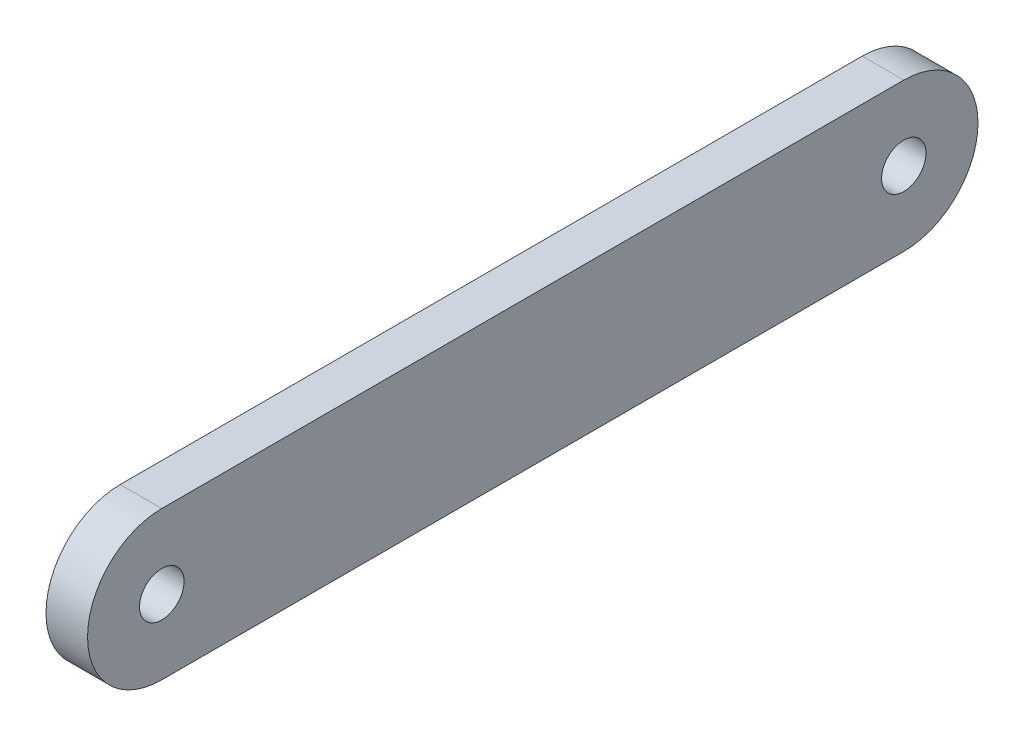
SolidWorks part; units mm, degrees
ref_plane "前视基准面" through (0, 0, 0) normal (0, 0, 1) x (1, 0, 0)
ref_plane "上视基准面" through (0, 0, 0) normal (0, 1, 0) x (1, 0, 0)
ref_plane "右视基准面" through (0, 0, 0) normal (1, 0, 0) x (0, 0, -1)
sketch "草图1" plane through (0, 0, 0) normal (1, 0, 0) x (0, 0, -1)
  line L0 (-250, 0) -> (250, 0) construction
  line L1 (-250, 50) -> (250, 50)
  line L2 (-250, -50) -> (250, -50)
  arc A0 (-250, 50) -> (-250, -50) centre (-250, 0) ccw
  arc A1 (250, -50) -> (250, 50) centre (250, 0) ccw
  circle A2 centre (250, 0) radius 15
  circle A3 centre (-250, 0) radius 15
  point P2 (0, 0)
  dimension "D2" = 50
  dimension "D3" = 30
  dimension "D4" = 30
  dimension "D1" = 500
extrude "凸台-拉伸1" add sketch "草图1" along normal blind 28
